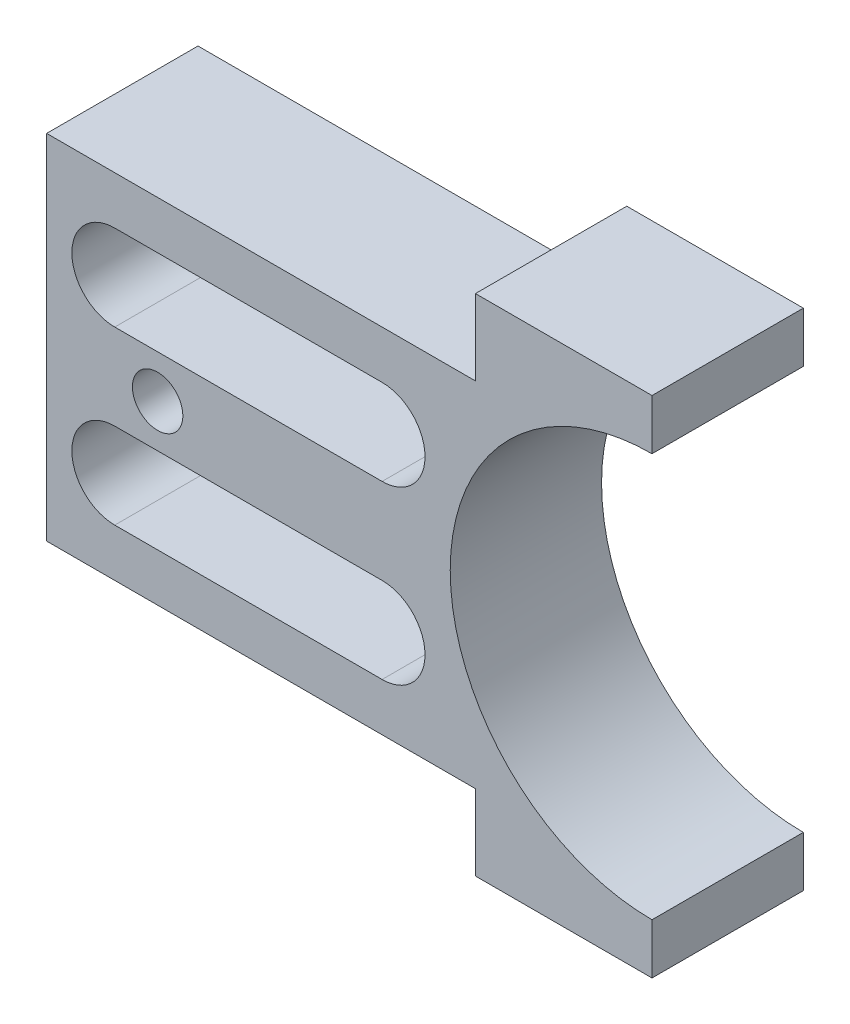
SolidWorks part; units mm, degrees
ref_plane "Спереди" through (0, 0, 0) normal (0, 0, 1) x (1, 0, 0)
ref_plane "Сверху" through (0, 0, 0) normal (0, 1, 0) x (1, 0, 0)
ref_plane "Справа" through (0, 0, 0) normal (1, 0, 0) x (0, 0, -1)
other "Configuration Table"
sketch "Эскиз1" plane through (0, 0, 0) normal (0, 0, 1) x (1, 0, 0)
  line L0 (60, 40) -> (60, 50)
  line L1 (60, 35) -> (-60, 35)
  line L2 (60, 35) -> (60, -35)
  line L3 (60, -35) -> (-60, -35)
  line L4 (-60, 35) -> (-60, -35)
  line L5 (60, 35) -> (-60, -35) construction
  line L6 (60, -35) -> (-60, 35) construction
  line L7 (60, -40) -> (60, -50)
  line L8 (60, -50) -> (25, -50)
  line L9 (25, -50) -> (25, 50)
  line L10 (25, 50) -> (60, 50)
  circle A0 centre (60, 0) radius 40
  point P0 (0, 0)
  point P8 (60, 50)
  point P9 (60, -50)
  point P10 (60, 40)
  point P11 (60, -40)
  point P12 (20, 0)
  point P17 (25, 0)
  dimension "D3" = 80
  dimension "D1" = 120
  dimension "D2" = 70
  dimension "D4" = 10
  dimension "D5" = 10
  dimension "D6" = 80
  dimension "D7" = 35
extrude "Бобышка-Вытянуть1" add sketch "Эскиз1" along normal blind 30 contours A0 L3 L9 L8 L7 | A0 L9 L3 | A0 L9 L1 L4 L3 | A0 L1 L9 | A0 L0 L10 L9 L1
chamfer "Фаска1" [suppressed] distance 15 angle 45
sketch "Эскиз3" plane through (0, 0, 30) normal (0, 0, 1) x (1, 0, 0)
  line L0 (-89.3592, 0) -> (65.5749, 0) construction
  line L1 (-46.5, 17) -> (6.5, 17) construction
  line L2 (-60, 35) -> (-60, -35) construction
  line L3 (-46.5, 25.5) -> (6.5, 25.5)
  line L4 (-46.5, 8.5) -> (6.5, 8.5)
  line L5 (-46.5, -17) -> (6.5, -17) construction
  line L6 (-46.5, -25.5) -> (6.5, -25.5)
  line L7 (-46.5, -8.5) -> (6.5, -8.5)
  arc A0 (-46.5, 25.5) -> (-46.5, 8.5) centre (-46.5, 17) ccw
  arc A1 (6.5, 8.5) -> (6.5, 25.5) centre (6.5, 17) ccw
  arc A2 (-46.5, -25.5) -> (-46.5, -8.5) centre (-46.5, -17) cw
  arc A3 (6.5, -8.5) -> (6.5, -25.5) centre (6.5, -17) cw
  point P7 (-20, 17)
  point P14 (-20, -17)
  dimension "D1" = 17
  dimension "D2" = 70
  dimension "D3" = 17
  dimension "D4" = 40
extrude "Вырез-Вытянуть1" cut sketch "Эскиз3" against normal through all
fillet "Скругление1" [suppressed] radius 2
sketch "Эскиз4" plane through (0, 0, 30) normal (0, 0, 1) x (1, 0, 0)
  line L0 (-60, 35) -> (-60, -35) construction
  circle A0 centre (-38, 0) radius 5
  point P4 (0, 0)
  dimension "D1" = 10
  dimension "D2" = 22
extrude "Вырез-Вытянуть2" cut sketch "Эскиз4" against normal through all
